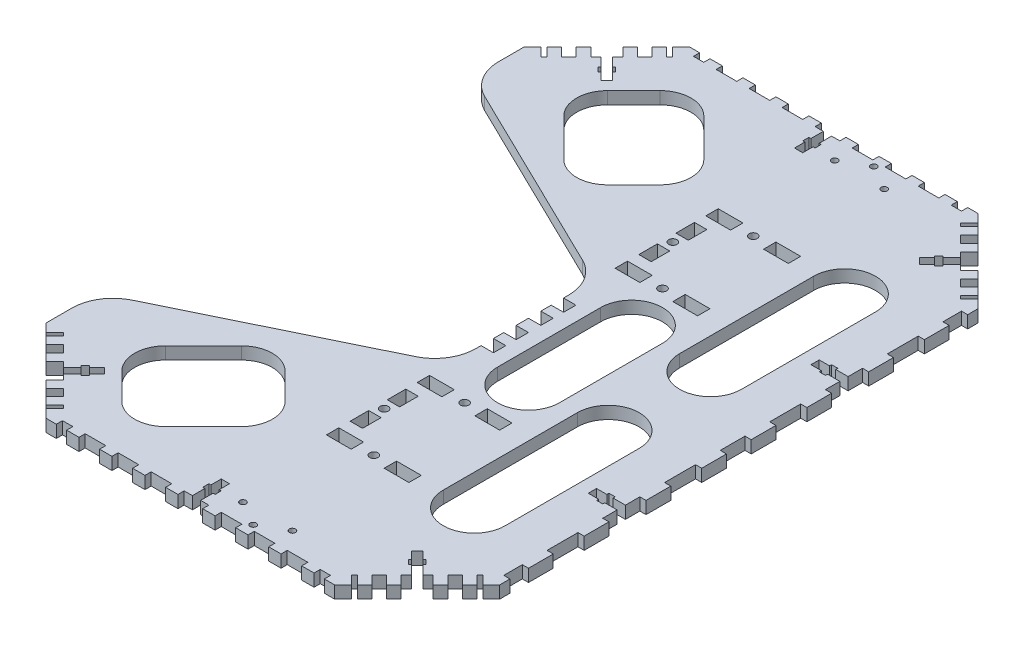
SolidWorks part; units mm, degrees
material "Balsa"
ref_plane "Plan de face" through (0, 0, 0) normal (0, 0, 1) x (1, 0, 0)
ref_plane "Plan de dessus" through (0, 0, 0) normal (0, 1, 0) x (1, 0, 0)
ref_plane "Plan de droite" through (0, 0, 0) normal (1, 0, 0) x (0, 0, -1)
sketch "Esquisse1" plane through (0, 0, 0) normal (0, 1, 0) x (1, 0, 0)
  line L1 (-137.5785, 87.498) -> (82.4215, 87.498)
  line L2 (-137.5785, 87.498) -> (-137.5785, -224.502)
  line L3 (-137.5785, -224.502) -> (82.4215, -224.502)
  line L4 (82.4215, 87.498) -> (82.4215, -224.502)
  dimension "D1" = 312
  dimension "D2" = 220
extrude "Boss.-Extru.1" add sketch "Esquisse1" along normal blind 6
sketch "Esquisse2" plane through (0, 6, 0) normal (0, 1, 0) x (1, 0, 0)
  line L0 (-10.5785, -116.502) -> (5.4215, -116.502) construction
  line L1 (-22.5785, -113.502) -> (-10.5785, -113.502)
  line L2 (-22.5785, -113.502) -> (-22.5785, -119.502)
  line L3 (-22.5785, -119.502) -> (-10.5785, -119.502)
  line L4 (-10.5785, -113.502) -> (-10.5785, -119.502)
  line L5 (5.4215, -113.502) -> (17.4215, -113.502)
  line L6 (5.4215, -113.502) -> (5.4215, -119.502)
  line L7 (5.4215, -119.502) -> (17.4215, -119.502)
  line L8 (17.4215, -113.502) -> (17.4215, -119.502)
  line L9 (82.4215, -68.502) -> (-137.5785, -68.502) construction
  line L10 (82.4215, -224.502) -> (82.4215, 87.498) construction
  line L11 (-137.5785, 87.498) -> (-137.5785, -224.502) construction
  line L12 (-6.2499, -138.502) -> (35.7501, -138.502) construction
  line L13 (17.4215, -163.502) -> (17.4215, -157.502)
  line L14 (5.4215, -163.502) -> (5.4215, -157.502)
  line L15 (5.4215, -163.502) -> (17.4215, -163.502)
  line L16 (-10.5785, -163.502) -> (-10.5785, -157.502)
  line L17 (-22.5785, -157.502) -> (-10.5785, -157.502)
  line L18 (-22.5785, -163.502) -> (-22.5785, -157.502)
  line L19 (-10.5785, -160.502) -> (5.4215, -160.502) construction
  line L20 (5.4215, -157.502) -> (17.4215, -157.502)
  line L21 (-22.5785, -163.502) -> (-10.5785, -163.502)
  line L22 (-10.5785, 23.498) -> (5.4215, 23.498) construction
  line L23 (-6.2499, 1.498) -> (35.7501, 1.498) construction
  line L24 (-10.5785, -20.502) -> (5.4215, -20.502) construction
  line L25 (-22.5785, 26.498) -> (-10.5785, 26.498)
  line L26 (5.4215, 20.498) -> (17.4215, 20.498)
  line L27 (-22.5785, 26.498) -> (-22.5785, 20.498)
  line L28 (-22.5785, 20.498) -> (-10.5785, 20.498)
  line L29 (-10.5785, 26.498) -> (-10.5785, 20.498)
  line L30 (5.4215, 26.498) -> (17.4215, 26.498)
  line L31 (5.4215, 26.498) -> (5.4215, 20.498)
  line L32 (17.4215, 26.498) -> (17.4215, 20.498)
  line L33 (17.4215, -23.502) -> (17.4215, -17.502)
  line L34 (5.4215, -17.502) -> (17.4215, -17.502)
  line L35 (5.4215, -23.502) -> (5.4215, -17.502)
  line L36 (5.4215, -23.502) -> (17.4215, -23.502)
  line L37 (-10.5785, -23.502) -> (-10.5785, -17.502)
  line L38 (-22.5785, -17.502) -> (-10.5785, -17.502)
  line L39 (-22.5785, -23.502) -> (-22.5785, -17.502)
  line L40 (-22.5785, -23.502) -> (-10.5785, -23.502)
  circle A0 centre (-2.5785, -116.502) radius 2
  circle A1 centre (-2.5785, -160.502) radius 2
  circle A2 centre (-2.5785, 23.498) radius 2
  circle A3 centre (-2.5785, -20.502) radius 2
  circle A4 centre (-14.5785, -212.002) radius 1.5
  circle A5 centre (-2.5785, -219.002) radius 1.5
  circle A6 centre (9.4215, -212.002) radius 1.5
  circle A7 centre (9.4215, 74.998) radius 1.5
  circle A8 centre (-2.5785, 81.998) radius 1.5
  circle A9 centre (-14.5785, 74.998) radius 1.5
  dimension "D5" = 4
  dimension "D9" = 3
  dimension "D10" = 3
  dimension "D11" = 3
  dimension "D1" = 12
  dimension "D2" = 12
  dimension "D3" = 6
  dimension "D4" = 16
  dimension "D6" = 19
  dimension "D7" = 45
  dimension "D8" = 115
extrude "Enlèv. mat.-Extru.1" cut sketch "Esquisse2" against normal through all
sketch "Esquisse3" plane through (0, 6, 0) normal (0, 1, 0) x (1, 0, 0)
  line L0 (-137.5785, 22.498) -> (-22.5785, -33.502)
  line L1 (-137.5785, 87.498) -> (-137.5785, -224.502) construction
  line L2 (-22.5785, -33.502) -> (-22.5785, -103.502)
  line L3 (-137.5785, 22.498) -> (-137.5785, -159.502)
  line L4 (-137.5785, -68.502) -> (-22.5785, -68.502) construction
  line L5 (-137.5785, -159.502) -> (-22.5785, -103.502)
  line L6 (82.4215, 87.498) -> (-137.5785, 87.498) construction
  dimension "D1" = 65
  dimension "D2" = 35
  dimension "D3" = 115
extrude "Enlèv. mat.-Extru.2" cut sketch "Esquisse3" against normal through all
fillet "Congé1" radius 20 4 edges at (-137.5785, 3, 159.502) (-22.5785, 3, 103.502) (-22.5785, 3, 33.502) (-137.5785, 3, -22.498)
fillet "Congé2" radius 40 4 edges at (-137.5785, 3, 224.502) (82.4215, 3, 224.502) (82.4215, 3, -87.498) (-137.5785, 3, -87.498)
sketch "Esquisse4" plane through (0, 6, 0) normal (0, 1, 0) x (1, 0, 0)
  line L0 (7.8686, 38.4495) -> (172.2037, 183.2192) construction
  line L1 (-97.5785, -224.502) -> (-137.5785, -184.502) construction
  line L3 (-137.5785, -184.502) -> (-97.5785, -224.502)
  arc A0 (-137.5785, -184.502) -> (-97.5785, -224.502) centre (-97.5785, -184.502) ccw
extrude "Enlèv. mat.-Extru.3" cut sketch "Esquisse4" against normal blind 6
ref_plane "Plan1" through (0, 0, 68.502) normal (0, 0, 1) x (1, 0, 0)
ref_plane "Plan2" through (-27.5785, 0, 0) normal (-1, 0, 0) x (0, 0, 1)
sketch "Esquisse7" plane through (0, 6, 0) normal (0, 1, 0) x (1, 0, 0)
  line L0 (-117.5785, -204.502) -> (-93.2137, -180.1372) construction
  line L2 (-114.7501, -198.8452) -> (-110.5075, -194.6025)
  line L3 (-97.5785, -224.502) -> (-137.5785, -184.502) construction
  line L4 (-121.4676, -200.6129) -> (-113.6895, -208.3911)
  line L5 (-121.4676, -200.6129) -> (-117.225, -196.3703)
  line L6 (-113.6895, -208.3911) -> (-109.4468, -204.1485)
  line L7 (-117.225, -196.3703) -> (-114.7501, -198.8452)
  line L8 (-125.0032, -197.0774) -> (-128.5387, -193.5419)
  line L9 (-125.0032, -197.0774) -> (-120.7605, -192.8348)
  line L10 (-128.5387, -193.5419) -> (-124.2961, -189.2992)
  line L11 (-120.7605, -192.8348) -> (-124.2961, -189.2992)
  line L12 (-110.1539, -211.9266) -> (-106.6184, -215.4622)
  line L13 (-110.1539, -211.9266) -> (-105.9113, -207.684)
  line L14 (-106.6184, -215.4622) -> (-102.3757, -211.2195)
  line L15 (-105.9113, -207.684) -> (-102.3757, -211.2195)
  line L16 (-101.6686, -220.4119) -> (-103.0829, -218.9977)
  line L17 (-101.6686, -220.4119) -> (-97.426, -216.1693)
  line L18 (-103.0829, -218.9977) -> (-98.8402, -214.7551)
  line L19 (-97.426, -216.1693) -> (-98.8402, -214.7551)
  line L20 (-132.0742, -190.0063) -> (-133.4884, -188.5921)
  line L21 (-132.0742, -190.0063) -> (-127.8316, -185.7637)
  line L22 (-133.4884, -188.5921) -> (-129.2458, -184.3495)
  line L23 (-127.8316, -185.7637) -> (-129.2458, -184.3495)
  line L24 (-111.9217, -201.6736) -> (-107.679, -197.431)
  line L25 (-105.5577, -195.3096) -> (-104.8506, -196.0167)
  line L26 (-111.2146, -193.8954) -> (-110.5075, -194.6025)
  line L27 (-111.2146, -193.8954) -> (-109.0933, -191.7741)
  line L28 (-106.9719, -198.1381) -> (-104.8506, -196.0167)
  line L29 (-109.0933, -191.7741) -> (-108.3862, -192.4812)
  line L30 (-111.9217, -201.6736) -> (-109.4468, -204.1485)
  line L31 (-108.3862, -192.4812) -> (-104.8506, -188.9457)
  line L32 (-105.5577, -195.3096) -> (-102.0222, -191.7741)
  line L33 (-104.8506, -188.9457) -> (-102.0222, -191.7741)
  line L34 (-107.679, -197.431) -> (-106.9719, -198.1381)
  dimension "D1" = 11
  dimension "D2" = 5
  dimension "D3" = 5
  dimension "D4" = 5
  dimension "D5" = 5
  dimension "D6" = 5
  dimension "D7" = 2
  dimension "D8" = 2
  dimension "D9" = 5
  dimension "D10" = 6
  dimension "D11" = 4
  dimension "D12" = 6
  dimension "D13" = 3
  dimension "D14" = 5
  dimension "D15" = 1
extrude "Enlèv. mat.-Extru.6" cut sketch "Esquisse7" against normal blind 6
sketch "Esquisse8" plane through (0, 6, 0) normal (0, 1, 0) x (1, 0, 0)
  line L0 (-137.5785, -184.502) -> (-97.5785, -224.502) construction
  line L1 (-100.4274, -200.44) -> (-42.3238, -142.3364) construction
  line L2 (-75.6787, -209.6324) -> (-109.6198, -175.6912)
  line L3 (-75.6787, -209.6324) -> (-36.0807, -170.0344)
  line L4 (-109.6198, -175.6912) -> (-70.0218, -136.0933)
  line L5 (-36.0807, -170.0344) -> (-70.0218, -136.0933)
  line L6 (-98.8402, -214.7551) -> (-102.3757, -211.2195) construction
  dimension "D1" = 56
  dimension "D2" = 48
  dimension "D3" = 20
extrude "Enlèv. mat.-Extru.7" cut sketch "Esquisse8" against normal through all
fillet "Congé3" radius 15 4 edges at (-75.6787, 3, 209.6324) (-109.6198, 3, 175.6912) (-36.0807, 3, 170.0344) (-70.0218, 3, 136.0933)
sketch "Esquisse9" plane through (0, 6, 0) normal (0, 1, 0) x (1, 0, 0)
  line L0 (-27.5785, -224.502) -> (-27.5785, -197.1737) construction
  line L2 (-97.5785, -224.502) -> (42.4215, -224.502) construction
  line L3 (-93.9004, -221.502) -> (40.4258, -221.502) construction
  line L5 (-33.5785, -221.502) -> (-21.5785, -221.502)
  line L6 (-33.5785, -221.502) -> (-33.5785, -224.502)
  line L7 (-33.5785, -224.502) -> (-21.5785, -224.502)
  line L8 (-21.5785, -221.502) -> (-21.5785, -224.502)
  line L9 (-39.5785, -221.502) -> (-49.5785, -221.502)
  line L10 (-39.5785, -221.502) -> (-39.5785, -224.502)
  line L11 (-39.5785, -224.502) -> (-49.5785, -224.502)
  line L12 (-49.5785, -221.502) -> (-49.5785, -224.502)
  line L13 (-55.5785, -221.502) -> (-65.5785, -221.502)
  line L14 (-55.5785, -221.502) -> (-55.5785, -224.502)
  line L15 (-55.5785, -224.502) -> (-65.5785, -224.502)
  line L16 (-65.5785, -221.502) -> (-65.5785, -224.502)
  line L17 (-71.5785, -221.502) -> (-81.5785, -221.502)
  line L18 (-71.5785, -221.502) -> (-71.5785, -224.502)
  line L19 (-71.5785, -224.502) -> (-81.5785, -224.502)
  line L20 (-81.5785, -221.502) -> (-81.5785, -224.502)
  line L21 (-92.5785, -221.502) -> (-87.5785, -221.502)
  line L22 (-92.5785, -221.502) -> (-92.5785, -224.502)
  line L23 (-92.5785, -224.502) -> (-87.5785, -224.502)
  line L24 (-87.5785, -221.502) -> (-87.5785, -224.502)
  line L25 (-15.5785, -221.502) -> (-5.5785, -221.502)
  line L26 (-15.5785, -221.502) -> (-15.5785, -224.502)
  line L27 (-15.5785, -224.502) -> (-5.5785, -224.502)
  line L28 (-5.5785, -221.502) -> (-5.5785, -224.502)
  line L29 (0.4215, -221.502) -> (10.4215, -221.502)
  line L30 (0.4215, -221.502) -> (0.4215, -224.502)
  line L31 (0.4215, -224.502) -> (10.4215, -224.502)
  line L32 (10.4215, -221.502) -> (10.4215, -224.502)
  line L33 (16.4215, -221.502) -> (26.4215, -221.502)
  line L34 (16.4215, -221.502) -> (16.4215, -224.502)
  line L35 (16.4215, -224.502) -> (26.4215, -224.502)
  line L36 (26.4215, -221.502) -> (26.4215, -224.502)
  line L37 (37.4215, -221.502) -> (32.4215, -221.502)
  line L38 (37.4215, -221.502) -> (37.4215, -224.502)
  line L39 (37.4215, -224.502) -> (32.4215, -224.502)
  line L40 (32.4215, -221.502) -> (32.4215, -224.502)
  dimension "D1" = 3
  dimension "D2" = 12
  dimension "D3" = 10
  dimension "D4" = 6
  dimension "D5" = 6
  dimension "D6" = 10
  dimension "D7" = 6
  dimension "D8" = 10
  dimension "D9" = 6
  dimension "D10" = 6
  dimension "D11" = 6
  dimension "D12" = 6
  dimension "D13" = 6
  dimension "D14" = 10
  dimension "D15" = 10
  dimension "D16" = 10
  dimension "D17" = 5
  dimension "D18" = 5
extrude "Enlèv. mat.-Extru.8" cut sketch "Esquisse9" against normal blind 6
sketch "Esquisse10" plane through (0, 6, 0) normal (0, 1, 0) x (1, 0, 0)
  line L0 (-27.5785, -221.502) -> (-27.5785, -195.7516) construction
  line L1 (-21.5785, -221.502) -> (-33.5785, -221.502) construction
  line L2 (-29.5785, -207.502) -> (-25.5785, -207.502)
  line L3 (-29.5785, -207.502) -> (-29.5785, -212.502)
  line L4 (-29.5785, -221.502) -> (-25.5785, -221.502)
  line L5 (-25.5785, -207.502) -> (-25.5785, -212.502)
  line L6 (-30.5785, -212.502) -> (-29.5785, -212.502)
  line L7 (-30.5785, -212.502) -> (-30.5785, -215.502)
  line L8 (-30.5785, -215.502) -> (-29.5785, -215.502)
  line L9 (-24.5785, -212.502) -> (-24.5785, -215.502)
  line L10 (-29.5785, -215.502) -> (-29.5785, -221.502)
  line L11 (-25.5785, -212.502) -> (-24.5785, -212.502)
  line L12 (-25.5785, -215.502) -> (-24.5785, -215.502)
  line L13 (-25.5785, -215.502) -> (-25.5785, -221.502)
  dimension "D1" = 6
  dimension "D2" = 3
  dimension "D3" = 5
  dimension "D4" = 4
  dimension "D5" = 1
extrude "Enlèv. mat.-Extru.9" cut sketch "Esquisse10" against normal blind 6
mirror "Symétrie3" about plane through (-27.5785, 0, 0) normal (-1, 0, 0) of "Enlèv. mat.-Extru.3", "Enlèv. mat.-Extru.6"
mirror "Symétrie1" about plane through (0, 0, 68.502) normal (0, 0, 1) of "Symétrie3", "Enlèv. mat.-Extru.7", "Congé3", "Enlèv. mat.-Extru.3", "Enlèv. mat.-Extru.6", "Enlèv. mat.-Extru.8", "Enlèv. mat.-Extru.9"
sketch "Esquisse5" plane through (0, 6, 0) normal (0, 1, 0) x (1, 0, 0)
  line L0 (-22.5785, 1.498) -> (-8.9165, 1.498) construction
  line L1 (-22.5785, -68.502) -> (-5.2188, -68.502) construction
  line L3 (-22.5785, 20.498) -> (-22.5785, -17.502) construction
  line L4 (-22.5785, -90.9959) -> (-22.5785, -46.0081) construction
  line L5 (-19.5785, 5.998) -> (-19.5785, -3.002) construction
  line L20 (-22.5785, -65.502) -> (-16.5785, -65.502)
  line L21 (-22.5785, -65.502) -> (-22.5785, -59.502)
  line L22 (-22.5785, -59.502) -> (-16.5785, -59.502)
  line L23 (-16.5785, -65.502) -> (-16.5785, -59.502)
  line L24 (-22.5785, -54.502) -> (-16.5785, -54.502)
  line L25 (-22.5785, -54.502) -> (-22.5785, -48.502)
  line L26 (-22.5785, -48.502) -> (-16.5785, -48.502)
  line L27 (-16.5785, -54.502) -> (-16.5785, -48.502)
  line L28 (-22.5785, -12.002) -> (-16.5785, -12.002)
  line L29 (-22.5785, -12.002) -> (-22.5785, -3.002)
  line L30 (-22.5785, -3.002) -> (-16.5785, -3.002)
  line L31 (-16.5785, -12.002) -> (-16.5785, -3.002)
  line L32 (-22.5785, 5.998) -> (-16.5785, 5.998)
  line L33 (-22.5785, 5.998) -> (-22.5785, 14.998)
  line L34 (-22.5785, 14.998) -> (-16.5785, 14.998)
  line L35 (-16.5785, 5.998) -> (-16.5785, 14.998)
  circle A0 centre (-19.5785, 1.498) radius 2
  dimension "D1" = 6
  dimension "D2" = 9
  dimension "D8" = 4
  dimension "D3" = 9
  dimension "D4" = 9
  dimension "D5" = 6
  dimension "D6" = 6
  dimension "D7" = 3
  dimension "D10" = 5
extrude "Enlèv. mat.-Extru.4" cut sketch "Esquisse5" against normal blind 6
mirror "Symétrie2" about plane through (0, 0, 68.502) normal (0, 0, 1) of "Enlèv. mat.-Extru.4"
sketch "Esquisse6" plane through (0, 6, 0) normal (0, 1, 0) x (1, 0, 0)
  line L0 (5.4215, -119.502) -> (5.4215, -17.502) construction
  line L1 (5.4215, -93.502) -> (5.4215, -43.502) construction
  line L2 (-9.5785, -93.502) -> (-9.5785, -43.502)
  line L3 (20.4215, -93.502) -> (20.4215, -43.502)
  line L4 (17.4215, -113.502) -> (5.4215, -113.502) construction
  line L5 (5.4215, -23.502) -> (17.4215, -23.502) construction
  line L6 (5.4215, -68.502) -> (82.4215, -68.502) construction
  line L7 (82.4215, -184.502) -> (82.4215, 47.498) construction
  line L8 (43.9215, -68.502) -> (43.9215, 50.4569) construction
  line L9 (43.9215, -68.502) -> (43.9215, -184.5972) construction
  line L10 (43.9215, -93.3125) -> (43.9215, -158.3125) construction
  line L11 (58.9215, -93.3125) -> (58.9215, -158.3125)
  line L12 (28.9215, -93.3125) -> (28.9215, -158.3125)
  line L13 (43.9215, -43.6915) -> (43.9215, 21.3085) construction
  line L14 (28.9215, -43.6915) -> (28.9215, 21.3085)
  line L15 (58.9215, -43.6915) -> (58.9215, 21.3085)
  arc A0 (-9.5785, -93.502) -> (20.4215, -93.502) centre (5.4215, -93.502) ccw
  arc A1 (20.4215, -43.502) -> (-9.5785, -43.502) centre (5.4215, -43.502) ccw
  arc A2 (58.9215, -93.3125) -> (28.9215, -93.3125) centre (43.9215, -93.3125) ccw
  arc A3 (28.9215, -158.3125) -> (58.9215, -158.3125) centre (43.9215, -158.3125) ccw
  arc A4 (28.9215, -43.6915) -> (58.9215, -43.6915) centre (43.9215, -43.6915) ccw
  arc A5 (58.9215, 21.3085) -> (28.9215, 21.3085) centre (43.9215, 21.3085) ccw
  point P6 (5.4215, -68.502)
  point P24 (43.9215, -125.8125)
  point P29 (43.9215, -11.1915)
  dimension "D3" = 15
  dimension "D4" = 15
  dimension "D5" = 15
  dimension "D1" = 20
  dimension "D2" = 20
  dimension "D6" = 65
  dimension "D7" = 65
extrude "Enlèv. mat.-Extru.5" cut sketch "Esquisse6" against normal blind 6
sketch "Esquisse11" plane through (0, 6, 0) normal (0, 1, 0) x (1, 0, 0)
  line L0 (82.4215, -68.502) -> (34.1514, -68.502) construction
  line L1 (82.4215, -184.502) -> (82.4215, 47.498) construction
  line L2 (79.4215, -176.6112) -> (79.4215, 41.1355) construction
  line L3 (79.4215, 39.6071) -> (79.4215, -178.1395) construction
  line L4 (82.4215, 33.498) -> (82.4215, 42.498)
  line L5 (82.4215, -62.502) -> (82.4215, -74.502)
  line L6 (82.4215, -74.502) -> (79.4215, -74.502)
  line L7 (79.4215, -62.502) -> (79.4215, -74.502)
  line L8 (82.4215, -86.502) -> (79.4215, -86.502)
  line L9 (82.4215, -86.502) -> (82.4215, -101.502)
  line L10 (82.4215, -101.502) -> (79.4215, -101.502)
  line L11 (79.4215, -86.502) -> (79.4215, -101.502)
  line L12 (79.4215, -113.502) -> (82.4215, -113.502)
  line L13 (79.4215, -113.502) -> (79.4215, -131.502)
  line L14 (79.4215, -131.502) -> (82.4215, -131.502)
  line L15 (82.4215, -113.502) -> (82.4215, -131.502)
  line L16 (79.4215, -143.502) -> (82.4215, -143.502)
  line L17 (79.4215, -143.502) -> (79.4215, -158.502)
  line L18 (79.4215, -158.502) -> (82.4215, -158.502)
  line L19 (82.4215, -143.502) -> (82.4215, -158.502)
  line L20 (79.4215, -170.502) -> (82.4215, -170.502)
  line L21 (79.4215, -170.502) -> (79.4215, -179.502)
  line L22 (79.4215, -179.502) -> (82.4215, -179.502)
  line L23 (82.4215, -170.502) -> (82.4215, -179.502)
  line L24 (79.4215, 42.498) -> (82.4215, 42.498)
  line L25 (79.4215, 33.498) -> (79.4215, 42.498)
  line L26 (79.4215, 33.498) -> (82.4215, 33.498)
  line L27 (82.4215, 6.498) -> (82.4215, 21.498)
  line L28 (79.4215, 21.498) -> (82.4215, 21.498)
  line L29 (79.4215, 6.498) -> (79.4215, 21.498)
  line L30 (79.4215, 6.498) -> (82.4215, 6.498)
  line L31 (82.4215, -23.502) -> (82.4215, -5.502)
  line L32 (79.4215, -5.502) -> (82.4215, -5.502)
  line L33 (79.4215, -23.502) -> (79.4215, -5.502)
  line L34 (79.4215, -23.502) -> (82.4215, -23.502)
  line L35 (79.4215, -50.502) -> (79.4215, -35.502)
  line L36 (82.4215, -35.502) -> (79.4215, -35.502)
  line L37 (82.4215, -50.502) -> (82.4215, -35.502)
  line L38 (82.4215, -50.502) -> (79.4215, -50.502)
  line L39 (82.4215, -62.502) -> (79.4215, -62.502)
  point P44 (79.4215, -68.502)
  dimension "D1" = 3
  dimension "D2" = 6
  dimension "D3" = 12
  dimension "D4" = 15
  dimension "D5" = 12
  dimension "D6" = 12
  dimension "D7" = 15
  dimension "D8" = 12
  dimension "D9" = 9
  dimension "D10" = 18
extrude "Enlèv. mat.-Extru.10" cut sketch "Esquisse11" against normal blind 6
sketch "Esquisse12" plane through (0, 6, 0) normal (0, 1, 0) x (1, 0, 0)
  line L0 (79.4215, -113.502) -> (79.4215, -131.502) construction
  line L1 (79.4215, -122.502) -> (56.6854, -122.502) construction
  line L2 (79.4215, -68.502) -> (37.0408, -68.502) construction
  line L3 (79.4215, -62.502) -> (79.4215, -74.502) construction
  line L4 (70.4215, -120.502) -> (70.4215, -119.502)
  line L5 (79.4215, -120.502) -> (73.4215, -120.502)
  line L6 (79.4215, -120.502) -> (79.4215, -124.502)
  line L7 (79.4215, -124.502) -> (73.4215, -124.502)
  line L8 (79.4215, -14.502) -> (56.6854, -14.502) construction
  line L9 (73.4215, -125.502) -> (70.4215, -125.502)
  line L10 (73.4215, -125.502) -> (73.4215, -124.502)
  line L11 (73.4215, -119.502) -> (70.4215, -119.502)
  line L12 (70.4215, -125.502) -> (70.4215, -124.502)
  line L13 (65.4215, -124.502) -> (70.4215, -124.502)
  line L14 (65.4215, -124.502) -> (65.4215, -120.502)
  line L15 (65.4215, -120.502) -> (70.4215, -120.502)
  line L16 (73.4215, -120.502) -> (73.4215, -119.502)
  line L17 (73.4215, -16.502) -> (73.4215, -17.502)
  line L18 (65.4215, -16.502) -> (70.4215, -16.502)
  line L19 (65.4215, -12.502) -> (65.4215, -16.502)
  line L20 (65.4215, -12.502) -> (70.4215, -12.502)
  line L21 (70.4215, -11.502) -> (70.4215, -12.502)
  line L22 (73.4215, -17.502) -> (70.4215, -17.502)
  line L23 (73.4215, -11.502) -> (73.4215, -12.502)
  line L24 (73.4215, -11.502) -> (70.4215, -11.502)
  line L25 (79.4215, -12.502) -> (73.4215, -12.502)
  line L26 (79.4215, -16.502) -> (79.4215, -12.502)
  line L27 (79.4215, -16.502) -> (73.4215, -16.502)
  line L28 (70.4215, -16.502) -> (70.4215, -17.502)
  dimension "D1" = 4
  dimension "D2" = 1
  dimension "D3" = 3
  dimension "D4" = 6
  dimension "D5" = 5
extrude "Enlèv. mat.-Extru.11" cut sketch "Esquisse12" against normal blind 6
